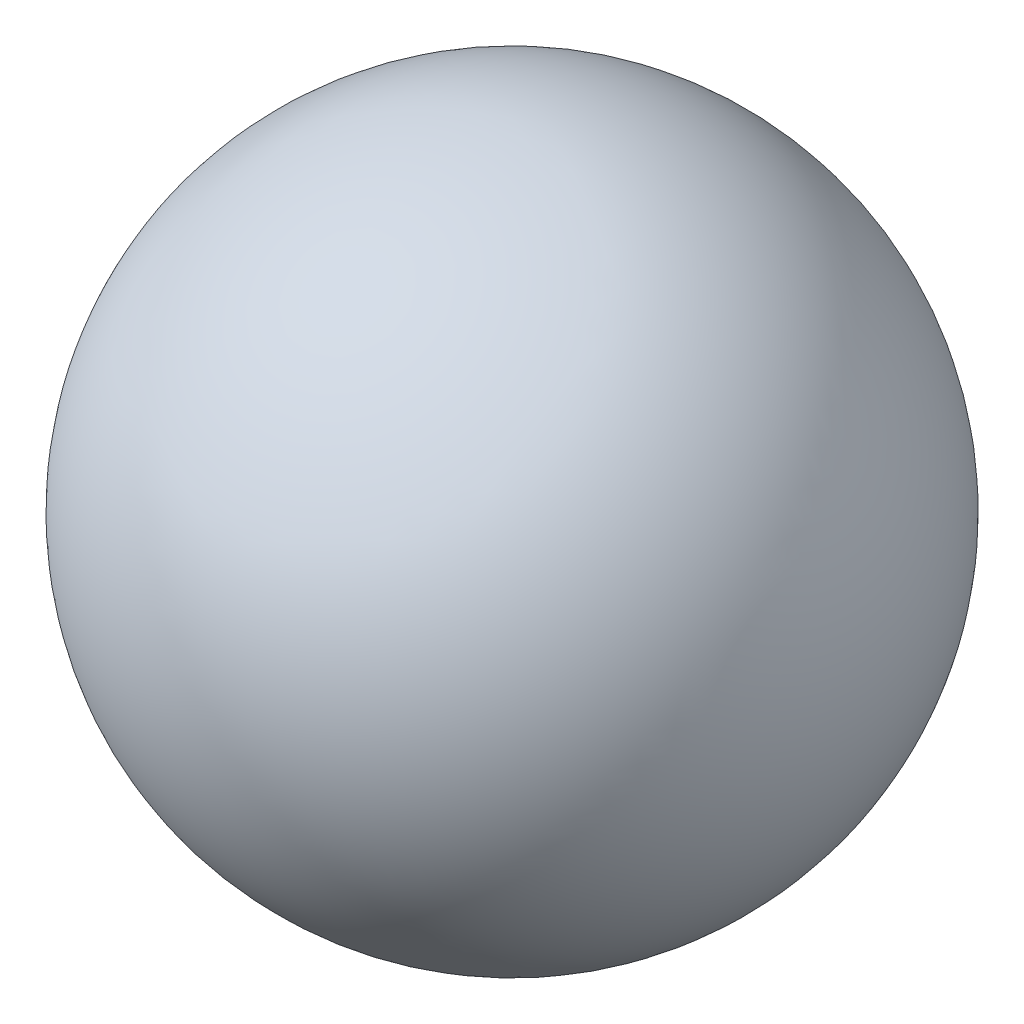
SolidWorks part; units mm, degrees
ref_plane "Front Plane" through (0, 0, 0) normal (0, 0, 1) x (1, 0, 0)
ref_plane "Top Plane" through (0, 0, 0) normal (0, 1, 0) x (1, 0, 0)
ref_plane "Right Plane" through (0, 0, 0) normal (1, 0, 0) x (0, 0, -1)
sketch "Sketch1" plane through (0, 0, 0) normal (0, 0, 1) x (1, 0, 0)
  line L0 (0, 0) -> (2.2, 0)
  line L1 (0, 0) -> (-2.2, 0)
  arc A0 (2.2, 0) -> (-2.2, 0) centre (0, 0) ccw
  dimension "D1" = 4.4
revolve "Revolve1" add sketch "Sketch1" angle 360 about L1
